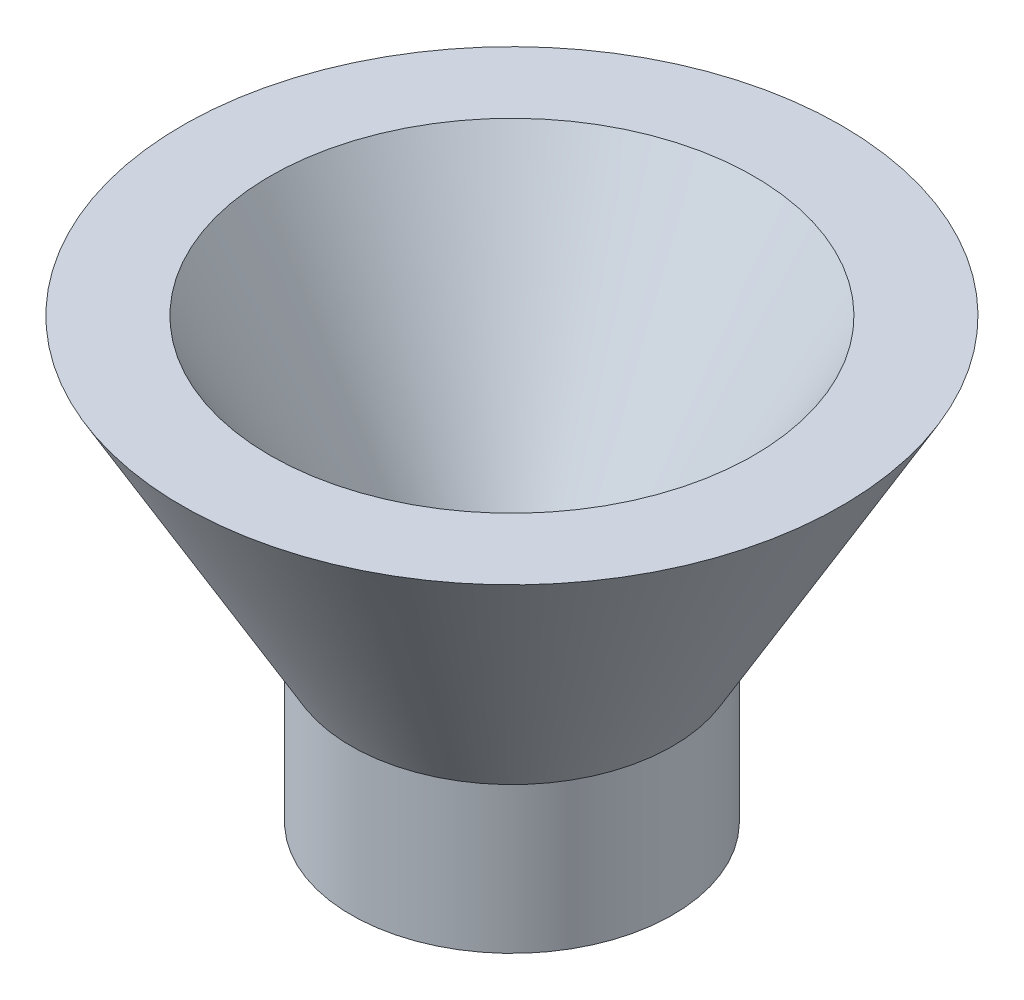
SolidWorks part; units mm, degrees
ref_plane "Plan de face" through (0, 0, 0) normal (0, 0, 1) x (1, 0, 0)
ref_plane "Plan de dessus" through (0, 0, 0) normal (0, 1, 0) x (1, 0, 0)
ref_plane "Plan de droite" through (0, 0, 0) normal (1, 0, 0) x (0, 0, -1)
sketch "Esquisse1" plane through (0, 0, 0) normal (0, 0, 1) x (1, 0, 0)
  line L0 (2.5, 0) -> (2.5, 5)
  line L1 (2.5, 5) -> (8.2735, 15)
  line L2 (8.2735, 15) -> (11.2735, 15)
  line L3 (11.2735, 15) -> (5.5, 5)
  line L4 (5.5, 5) -> (5.5, 0)
  line L5 (5.5, 0) -> (2.5, 0)
  line L6 (0, 0) -> (0, 28.6893) construction
  line L7 (2.5, 0) -> (0, 0) construction
  dimension "D1" = 5
  dimension "D2" = 3
  dimension "D3" = 3
  dimension "D4" = 5
  dimension "D5" = 150
  dimension "D6" = 10
revolve "Révolution1" add sketch "Esquisse1" angle 360 about L6
